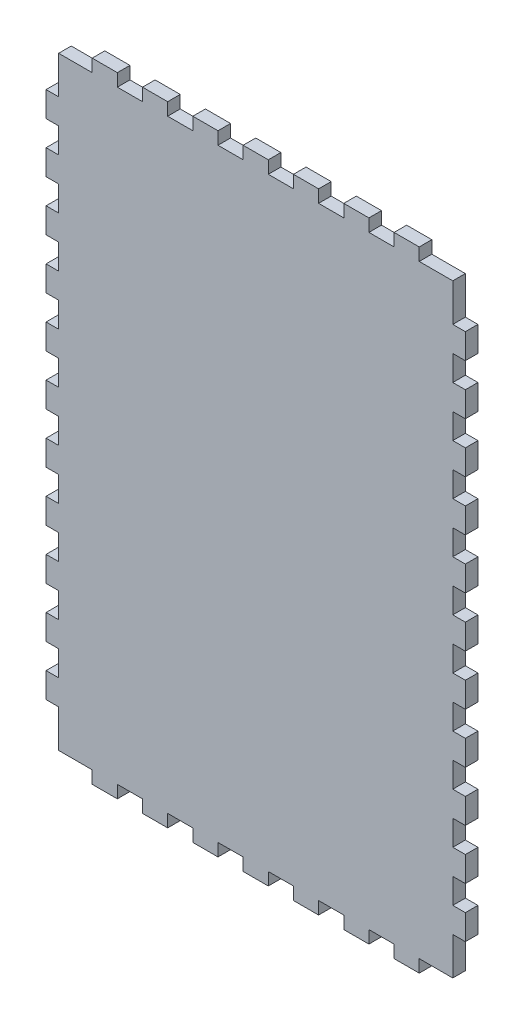
SolidWorks part; units mm, degrees
ref_plane "Front Plane" through (0, 0, 0) normal (0, 0, 1) x (1, 0, 0)
ref_plane "Top Plane" through (0, 0, 0) normal (0, 1, 0) x (1, 0, 0)
ref_plane "Right Plane" through (0, 0, 0) normal (1, 0, 0) x (0, 0, -1)
sketch "Model" plane through (0, 0, 0) normal (0, 0, 1) x (1, 0, 0)
  line L0 (512, 600) -> (512, 582)
  line L1 (512, 582) -> (506, 582)
  line L2 (506, 582) -> (506, 570)
  line L3 (506, 570) -> (512, 570)
  line L4 (512, 570) -> (512, 558)
  line L5 (512, 558) -> (506, 558)
  line L6 (506, 558) -> (506, 546)
  line L7 (506, 546) -> (512, 546)
  line L8 (512, 546) -> (512, 534)
  line L9 (512, 534) -> (506, 534)
  line L10 (506, 534) -> (506, 522)
  line L11 (506, 522) -> (512, 522)
  line L12 (512, 522) -> (512, 510)
  line L13 (512, 510) -> (506, 510)
  line L14 (506, 510) -> (506, 498)
  line L15 (506, 498) -> (512, 498)
  line L16 (512, 498) -> (512, 486)
  line L17 (512, 486) -> (506, 486)
  line L18 (506, 486) -> (506, 474)
  line L19 (506, 474) -> (512, 474)
  line L20 (512, 474) -> (512, 462)
  line L21 (512, 462) -> (506, 462)
  line L22 (506, 462) -> (506, 450)
  line L23 (506, 450) -> (512, 450)
  line L24 (512, 450) -> (512, 438)
  line L25 (512, 438) -> (506, 438)
  line L26 (506, 438) -> (506, 426)
  line L27 (506, 426) -> (512, 426)
  line L28 (512, 426) -> (512, 414)
  line L29 (512, 414) -> (506, 414)
  line L30 (506, 414) -> (506, 402)
  line L31 (506, 402) -> (512, 402)
  line L32 (512, 402) -> (512, 390)
  line L33 (512, 390) -> (506, 390)
  line L34 (506, 390) -> (506, 378)
  line L35 (506, 378) -> (512, 378)
  line L36 (512, 378) -> (512, 366)
  line L37 (512, 366) -> (506, 366)
  line L38 (506, 366) -> (506, 354)
  line L39 (506, 354) -> (512, 354)
  line L40 (512, 354) -> (512, 342)
  line L41 (512, 342) -> (506, 342)
  line L42 (506, 342) -> (506, 330)
  line L43 (506, 330) -> (512, 330)
  line L44 (512, 330) -> (512, 318)
  line L45 (512, 318) -> (512, 312)
  line L46 (512, 312) -> (528, 312)
  line L47 (528, 312) -> (528, 306)
  line L48 (528, 306) -> (540, 306)
  line L49 (540, 306) -> (540, 312)
  line L50 (540, 312) -> (552, 312)
  line L51 (552, 312) -> (552, 306)
  line L52 (552, 306) -> (564, 306)
  line L53 (564, 306) -> (564, 312)
  line L54 (564, 312) -> (576, 312)
  line L55 (576, 312) -> (576, 306)
  line L56 (576, 306) -> (588, 306)
  line L57 (588, 306) -> (588, 312)
  line L58 (588, 312) -> (600, 312)
  line L59 (600, 312) -> (600, 306)
  line L60 (600, 306) -> (612, 306)
  line L61 (612, 306) -> (612, 312)
  line L62 (612, 312) -> (624, 312)
  line L63 (624, 312) -> (624, 306)
  line L64 (624, 306) -> (636, 306)
  line L65 (636, 306) -> (636, 312)
  line L66 (636, 312) -> (648, 312)
  line L67 (648, 312) -> (648, 306)
  line L68 (648, 306) -> (660, 306)
  line L69 (660, 306) -> (660, 312)
  line L70 (660, 312) -> (672, 312)
  line L71 (672, 312) -> (672, 306)
  line L72 (672, 306) -> (684, 306)
  line L73 (684, 306) -> (684, 312)
  line L74 (684, 312) -> (696, 312)
  line L75 (696, 312) -> (700, 312)
  line L76 (700, 312) -> (700, 330)
  line L77 (700, 330) -> (706, 330)
  line L78 (706, 330) -> (706, 342)
  line L79 (706, 342) -> (700, 342)
  line L80 (700, 342) -> (700, 354)
  line L81 (700, 354) -> (706, 354)
  line L82 (706, 354) -> (706, 366)
  line L83 (706, 366) -> (700, 366)
  line L84 (700, 366) -> (700, 378)
  line L85 (700, 378) -> (706, 378)
  line L86 (706, 378) -> (706, 390)
  line L87 (706, 390) -> (700, 390)
  line L88 (700, 390) -> (700, 402)
  line L89 (700, 402) -> (706, 402)
  line L90 (706, 402) -> (706, 414)
  line L91 (706, 414) -> (700, 414)
  line L92 (700, 414) -> (700, 426)
  line L93 (700, 426) -> (706, 426)
  line L94 (706, 426) -> (706, 438)
  line L95 (706, 438) -> (700, 438)
  line L96 (700, 438) -> (700, 450)
  line L97 (700, 450) -> (706, 450)
  line L98 (706, 450) -> (706, 462)
  line L99 (706, 462) -> (700, 462)
  line L100 (700, 462) -> (700, 474)
  line L101 (700, 474) -> (706, 474)
  line L102 (706, 474) -> (706, 486)
  line L103 (706, 486) -> (700, 486)
  line L104 (700, 486) -> (700, 498)
  line L105 (700, 498) -> (706, 498)
  line L106 (706, 498) -> (706, 510)
  line L107 (706, 510) -> (700, 510)
  line L108 (700, 510) -> (700, 522)
  line L109 (700, 522) -> (706, 522)
  line L110 (706, 522) -> (706, 534)
  line L111 (706, 534) -> (700, 534)
  line L112 (700, 534) -> (700, 546)
  line L113 (700, 546) -> (706, 546)
  line L114 (706, 546) -> (706, 558)
  line L115 (706, 558) -> (700, 558)
  line L116 (700, 558) -> (700, 570)
  line L117 (700, 570) -> (706, 570)
  line L118 (706, 570) -> (706, 582)
  line L119 (706, 582) -> (700, 582)
  line L120 (700, 582) -> (700, 594)
  line L121 (700, 594) -> (700, 600)
  line L122 (700, 600) -> (684, 600)
  line L123 (684, 600) -> (684, 606)
  line L124 (684, 606) -> (672, 606)
  line L125 (672, 606) -> (672, 600)
  line L126 (672, 600) -> (660, 600)
  line L127 (660, 600) -> (660, 606)
  line L128 (660, 606) -> (648, 606)
  line L129 (648, 606) -> (648, 600)
  line L130 (648, 600) -> (636, 600)
  line L131 (636, 600) -> (636, 606)
  line L132 (636, 606) -> (624, 606)
  line L133 (624, 606) -> (624, 600)
  line L134 (624, 600) -> (612, 600)
  line L135 (612, 600) -> (612, 606)
  line L136 (612, 606) -> (600, 606)
  line L137 (600, 606) -> (600, 600)
  line L138 (600, 600) -> (588, 600)
  line L139 (588, 600) -> (588, 606)
  line L140 (588, 606) -> (576, 606)
  line L141 (576, 606) -> (576, 600)
  line L142 (576, 600) -> (564, 600)
  line L143 (564, 600) -> (564, 606)
  line L144 (564, 606) -> (552, 606)
  line L145 (552, 606) -> (552, 600)
  line L146 (552, 600) -> (540, 600)
  line L147 (540, 600) -> (540, 606)
  line L148 (540, 606) -> (528, 606)
  line L149 (528, 606) -> (528, 600)
  line L150 (528, 600) -> (516, 600)
  line L151 (516, 600) -> (512, 600)
extrude "Boss-Extrude1" add sketch "Model" along normal blind 6
